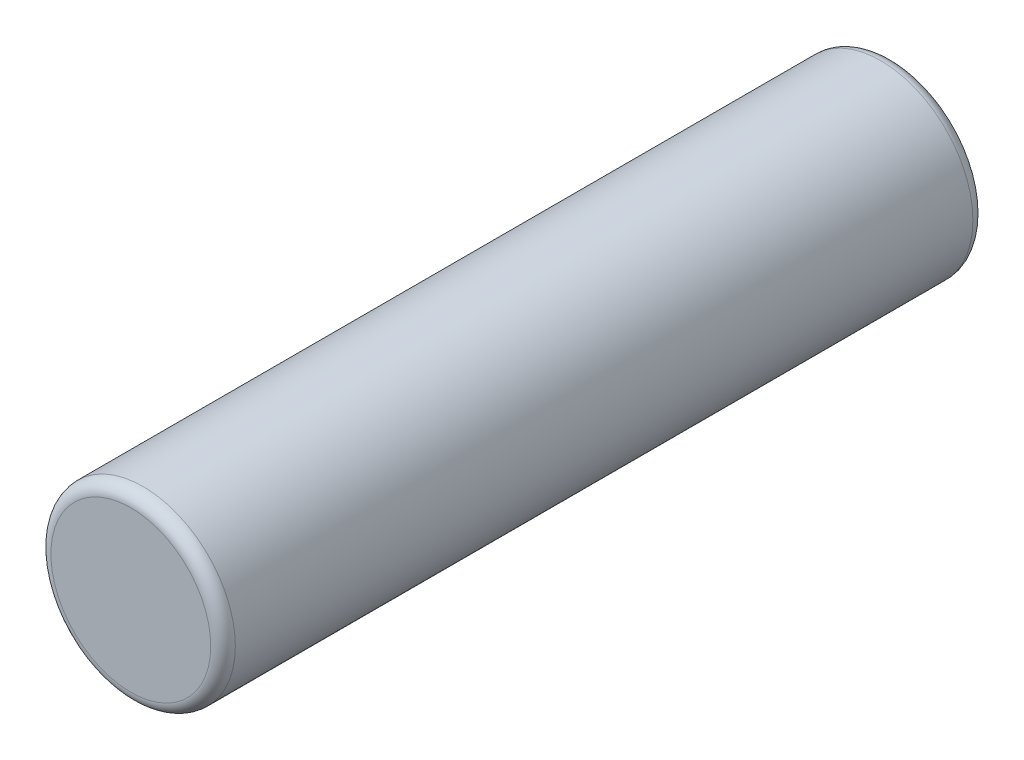
SolidWorks part; units mm, degrees
ref_plane "Front Plane" through (0, 0, 0) normal (0, 0, 1) x (1, 0, 0)
ref_plane "Top Plane" through (0, 0, 0) normal (0, 1, 0) x (1, 0, 0)
ref_plane "Right Plane" through (0, 0, 0) normal (1, 0, 0) x (0, 0, -1)
sketch "Sketch1" plane through (0, 0, 0) normal (0, 0, 1) x (1, 0, 0)
  circle A0 centre (0, 0) radius 7.5
  dimension "D1" = 15
extrude "Boss-Extrude1" add sketch "Sketch1" along normal blind 62
fillet "Fillet1" radius 1 2 edges at (7.5, 0, 0) (7.5, 0, 62)
